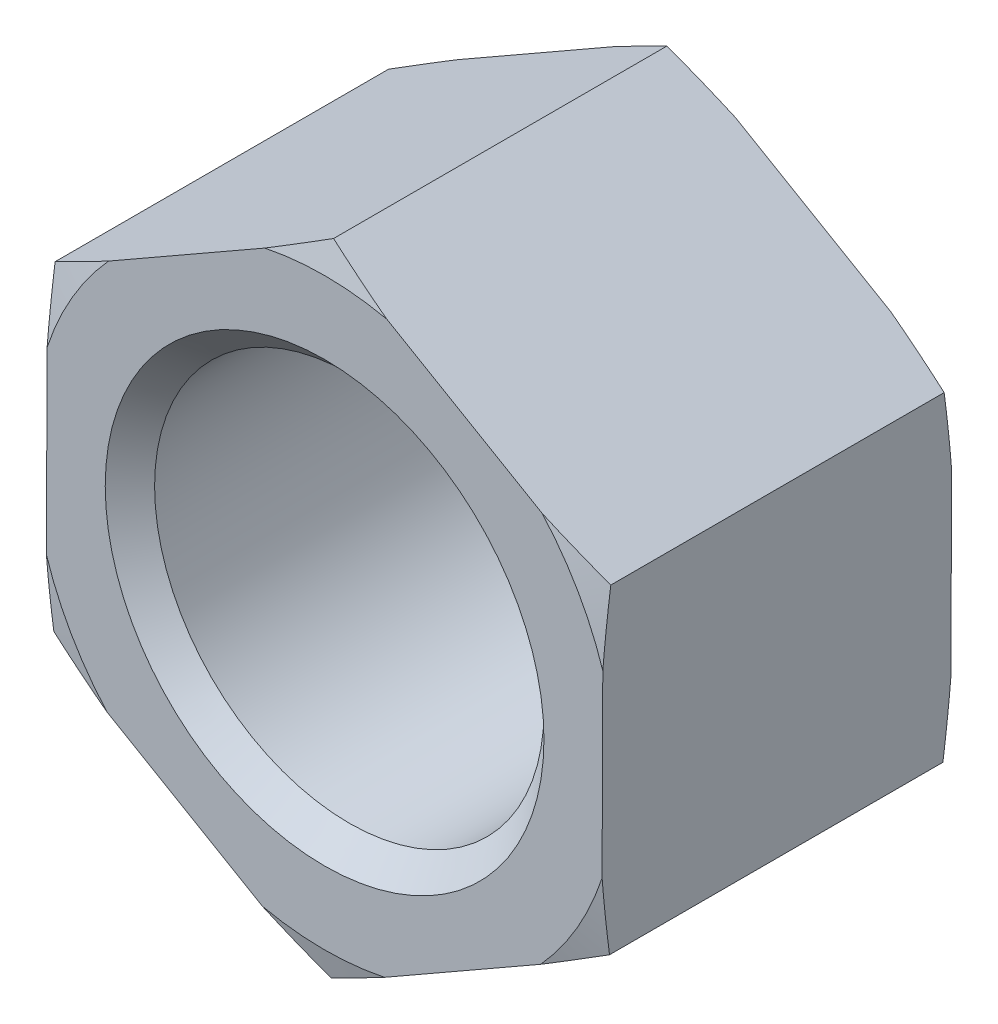
SolidWorks part; units mm, degrees
extrude "基体-拉伸" add sketch "草图1" along normal blind 21.5
sketch "草图1" plane through (0, 0, 0) normal (0, 0, 1) x (1, 0, 0)
  line L0 (-26.8088, 0) -> (37.1748, 0) construction
  line L1 (0, 25.0215) -> (0, -25.0215) construction
  line L3 (0.0778, 19.7748) -> (-17.0866, 9.9548)
  line L4 (-17.0866, 9.9548) -> (-17.1644, -9.8201)
  line L5 (-17.1644, -9.8201) -> (-0.0778, -19.7748)
  line L6 (-0.0778, -19.7748) -> (17.0866, -9.9548)
  line L7 (17.0866, -9.9548) -> (17.1644, 9.8201)
  line L8 (17.1644, 9.8201) -> (0.0778, 19.7748)
  circle A0 centre (0, 0) radius 17.1257 construction
  circle A1 centre (0, 0) radius 12
  dimension "D" = 24
  dimension "e" = 39.55
cosmetic thread "装饰螺纹线1"
chamfer "倒角1" distance 1.5214 angle 45 2 edges at (12, 0, 0) (12, 0, 21.5)
material "不锈钢"
ref_plane "基准面1" through (0, 0, 0) normal (0, 0, 1) x (1, 0, 0)
ref_plane "基准面2" through (0, 0, 0) normal (0, 1, 0) x (1, 0, 0)
ref_plane "基准面3" through (0, 0, 0) normal (1, 0, 0) x (0, 0, -1)
sketch "尺寸草图" plane through (0, 0, 0) normal (0, 0, 1) x (1, 0, 0)
  line L0 (0, 0) -> (11.5249, 0)
  line L1 (11.5249, 0) -> (37.4249, 0)
  line L2 (37.4249, 0) -> (70.7249, 0)
  line L3 (-22.8571, 0) -> (0, 0)
  point P3 (24, 0)
  point P4 (1.5, 0)
  point P5 (39.55, 0)
  point P6 (21.5, 0)
  point P7 (6.4, 0)
  point P8 (36, 0)
  dimension "D" = 24
  dimension "e" = 39.55
  dimension "P" = 1.5
  dimension "m" = 21.5
  dimension "mw" = 6.4
  dimension "s" = 36
  dimension "da" = 25.9
  dimension "dw" = 33.3
  dimension "D1" = 22.8571
sketch "草图2" plane through (0, 0, 0) normal (0, 0, -1) x (-1, 0, 0)
  circle A0 centre (0, 0) radius 18
  circle A1 centre (0, 0) radius 12 construction
  dimension "s" = 36
extrude "切除-拉伸1" cut sketch "草图2" against normal through all draft 75 flip side to cut
sketch "草图3" plane through (0, 0, 21.5) normal (0, 0, 1) x (1, 0, 0)
  circle A0 centre (0, 0) radius 18
  dimension "D1" = 36
extrude "切除-拉伸2" cut sketch "草图3" against normal through all draft 75 flip side to cut
equation "\"e@草图1\" = \"e@尺寸草图\""
equation "\"D1@尺寸草图\" = \"D@尺寸草图\" / 1.05"
equation "\"D@草图1\" = \"D@尺寸草图\""
equation "\"m@基体-拉伸\" = \"m@尺寸草图\""
equation "\"D1@草图3\" = \"s@尺寸草图\""
equation "\"s@草图2\" = \"s@尺寸草图\""
equation "\"D2@装饰螺纹线1\" =\"D@尺寸草图\""
equation "\"D1@倒角1\" =  ( \"da@尺寸草图\" - \"D1@尺寸草图\" )  / 2"
